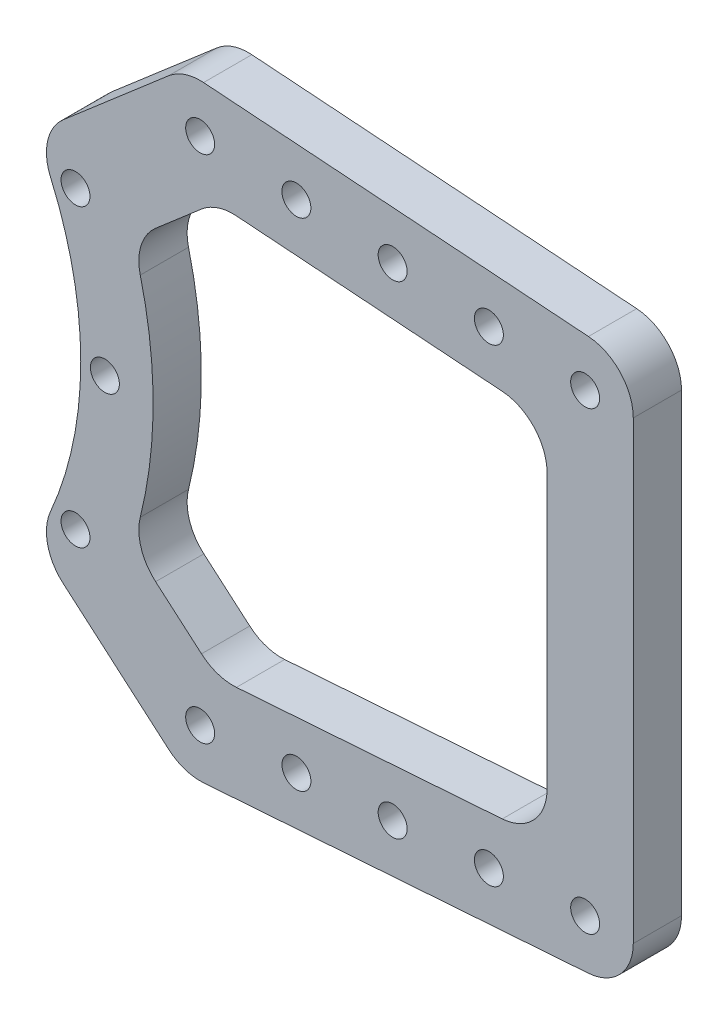
SolidWorks part; units mm, degrees
ref_plane "前视基准面" through (0, 0, 0) normal (0, 0, 1) x (1, 0, 0)
ref_plane "上视基准面" through (0, 0, 0) normal (0, 1, 0) x (1, 0, 0)
ref_plane "右视基准面" through (0, 0, 0) normal (1, 0, 0) x (0, 0, -1)
other "Configuration Table"
sketch "草图3" plane through (0, 0, 0) normal (0, 0, 1) x (1, 0, 0)
  line L0 (36.9552, -15.3073) -> (49.8729, -26.4376)
  line L1 (49.8729, -26.4376) -> (99.7459, -22.8753)
  line L2 (99.7459, -22.8753) -> (109.9739, -12.4372)
  line L3 (36.9552, 15.3073) -> (49.8729, 26.4376)
  line L4 (49.8729, 26.4376) -> (99.7459, 22.8753)
  line L5 (99.7459, 22.8753) -> (109.9739, 12.4372)
  line L6 (32.4388, -18.0159) -> (48.1718, -31.5719)
  line L7 (48.1718, -31.5719) -> (101.9915, -27.7276)
  line L8 (101.9915, -27.7276) -> (114.1851, -15.2836)
  line L9 (40.2189, -11.5195) -> (51.5741, -21.3034)
  line L10 (51.5741, -21.3034) -> (97.5003, -18.023)
  line L11 (97.5003, -18.023) -> (106.4026, -8.9378)
  line L12 (40.2189, 11.5195) -> (51.5741, 21.3034)
  line L13 (51.5741, 21.3034) -> (97.5003, 18.023)
  line L14 (97.5003, 18.023) -> (106.4026, 8.9378)
  line L15 (32.0167, 17.6522) -> (48.1718, 31.5719)
  line L16 (48.1718, 31.5719) -> (101.9915, 27.7276)
  line L17 (101.9915, 27.7276) -> (114.1732, 15.2957)
  line L18 (33.6914, -19.0952) -> (48.1718, -31.5719) construction
  line L19 (33.6914, 19.0952) -> (48.1718, 31.5719) construction
  line L20 (101.9915, -27.7276) -> (113.5452, -15.9366) construction
  line L21 (101.9915, 27.7276) -> (113.5452, 15.9366) construction
  line L22 (112.379, 17.1268) -> (115.1724, 14.276)
  circle A0 centre (140, 0) radius 32.5
  circle A1 centre (0, 0) radius 40
  circle A2 centre (140, 0) radius 35
  circle A4 centre (0, 0) radius 45
  circle A5 centre (0, 0) radius 37.5
  circle A6 centre (140, 0) radius 30
  dimension "D5" = 75
  dimension "D6" = 60
  dimension "D1" = 5
  dimension "D2" = 5
  dimension "D3" = 5
  dimension "D4" = 5
extrude "凸台-拉伸1" add sketch "草图3" along normal blind 15
fillet "圆角1" radius 5 1 edges at (101.9915, 27.7276, 7.5)
fillet "圆角2" radius 5 1 edges at (114.1851, 15.2836, 7.5)
fillet "圆角3" radius 5 1 edges at (114.1851, -15.2836, 7.5)
fillet "圆角4" radius 5 1 edges at (101.9915, -27.7276, 7.5)
fillet "圆角5" radius 5 1 edges at (48.1718, -31.5719, 7.5)
fillet "圆角6" radius 5 1 edges at (48.1718, 31.5719, 7.5)
fillet "圆角7" radius 5 1 edges at (32.7436, -18.2785, 7.5)
fillet "圆角8" radius 5 1 edges at (32.7436, 18.2785, 7.5)
fillet "圆角9" radius 5 1 edges at (97.5003, -18.023, 7.5)
fillet "圆角10" radius 5 1 edges at (106.2123, -9.132, 7.5)
fillet "圆角11" radius 5 1 edges at (106.2123, 9.132, 7.5)
fillet "圆角12" radius 5 1 edges at (97.5003, 18.023, 7.5)
fillet "圆角13" radius 5 1 edges at (51.5741, -21.3034, 7.5)
fillet "圆角14" radius 5 1 edges at (42.8391, -13.7771, 7.5)
fillet "圆角15" radius 5 1 edges at (42.8391, 13.7771, 7.5)
fillet "圆角16" radius 5 1 edges at (51.5741, 21.3034, 7.5)
sketch "草图5" plane through (0, 0, 0) normal (0, 0, -1) x (-1, 0, 0)
  circle A0 centre (-36.9552, 15.3073) radius 1.5
  circle A1 centre (-40, 0) radius 1.5
  circle A2 centre (-36.9552, -15.3073) radius 1.5
  circle A3 centre (-49.8729, -26.4376) radius 1.5
  circle A4 centre (-49.8729, 26.4376) radius 1.5
  circle A5 centre (-99.7459, 22.8753) radius 1.5
  circle A6 centre (-99.7459, -22.8753) radius 1.5
  circle A7 centre (-109.9739, 12.4372) radius 1.5
  circle A8 centre (-107.5, 0) radius 1.5
  circle A9 centre (-109.9739, -12.4372) radius 1.5
  circle A10 centre (-59.8475, 25.7252) radius 1.5
  circle A11 centre (-69.8221, 25.0127) radius 1.5
  circle A12 centre (-79.7967, 24.3002) radius 1.5
  circle A13 centre (-89.7713, 23.5878) radius 1.5
  circle A14 centre (-89.7713, -23.5878) radius 1.5
  circle A15 centre (-79.7967, -24.3002) radius 1.5
  circle A16 centre (-69.8221, -25.0127) radius 1.5
  circle A17 centre (-59.8475, -25.7252) radius 1.5
extrude "切除-拉伸1" cut sketch "草图5" against normal blind 15
sketch "草图6" plane through (0, 0, 15) normal (0, 0, 1) x (1, 0, 0)
  line L0 (100.1021, 27.8626) -> (100.1021, -27.8626)
  line L1 (100.1021, 27.8626) -> (115.1226, 26.777)
  line L2 (4.9746, 34.6447) -> (140, 25) construction
  line L3 (115.1226, 26.777) -> (132.6157, -67.8734)
  line L4 (132.6157, -67.8734) -> (100.1021, -27.8626)
  line L5 (99.7459, 22.8753) -> (89.7713, 23.5878)
  line L6 (99.7459, -22.8753) -> (89.7713, -23.5878)
  line L7 (94.7586, 23.2315) -> (94.7586, -23.2315)
  line L8 (94.7586, 23.2315) -> (94.7586, 28.2443)
  line L9 (50.2292, 31.4249) -> (100.1021, 27.8626) construction
  line L10 (94.7586, 28.2443) -> (100.1021, 27.8626)
  line L11 (94.7586, -23.2315) -> (94.7586, -28.2443)
  line L12 (50.2292, -31.4249) -> (100.1021, -27.8626) construction
  line L13 (94.7586, -28.2443) -> (100.1021, -27.8626)
  circle M8 centre (109.9739, -12.4372) radius 1.5
  circle M13 centre (107.5, 0) radius 1.5
  circle M14 centre (109.9739, 12.4372) radius 1.5
  circle M15 centre (99.7459, -22.8753) radius 1.5
  circle M16 centre (99.7459, 22.8753) radius 1.5
  line M24 (53.6315, 21.1564) -> (95.6109, 18.1579)
  arc M25 (95.6109, 18.1579) -> (98.826, 16.67) centre (95.2547, 13.1706) cw
  line M26 (98.826, 16.67) -> (104.2974, 11.0863)
  arc M27 (104.2974, 11.0863) -> (105.6353, 6.6385) centre (100.7261, 7.5869) cw
  arc M28 (105.6353, 6.6385) -> (105.6353, -6.6385) centre (140, 0) ccw
  arc M29 (105.6353, -6.6385) -> (104.2974, -11.0863) centre (100.7261, -7.5869) cw
  line M30 (104.2974, -11.0863) -> (98.826, -16.67)
  arc M31 (98.826, -16.67) -> (95.6109, -18.1579) centre (95.2547, -13.1706) cw
  line M32 (95.6109, -18.1579) -> (53.6315, -21.1564)
  line M45 (50.2292, -31.4249) -> (100.1021, -27.8626)
  arc M46 (100.1021, -27.8626) -> (103.3172, -26.3747) centre (99.7459, -22.8753) ccw
  line M47 (103.3172, -26.3747) -> (111.6554, -17.8652)
  arc M48 (111.6554, -17.8652) -> (112.6435, -12.3136) centre (108.0841, -14.3658) ccw
  arc M49 (112.6435, -12.3136) -> (112.6435, 12.3136) centre (140, 0) cw
  arc M50 (112.6435, 12.3136) -> (111.6554, 17.8652) centre (108.0841, 14.3658) ccw
  line M51 (111.6554, 17.8652) -> (103.3172, 26.3747)
  arc M52 (103.3172, 26.3747) -> (100.1021, 27.8626) centre (99.7459, 22.8753) ccw
  line M53 (100.1021, 27.8626) -> (50.2292, 31.4249)
extrude "切除-拉伸5" cut sketch "草图6" against normal blind 15 contours L0 M52 M16 M26 M27 M28 M29 M30 M15 M46 M47 M48 M49 M50 M51 M13 M14 M8 | L7 L6 L0 M32 M15 M30 M31 | L6 L11 L0 M45 M15 | L5 L7 L0 M24 M25 M26 M16 | L8 L5 L0 M16 M53
sketch "草图7" plane through (0, 0, 15) normal (0, 0, 1) x (1, 0, 0)
  line L0 (94.7586, 18.2188) -> (85.8268, 18.8568)
  line L1 (94.7586, 28.2443) -> (85.8268, 28.2443)
  line L2 (94.7586, 28.2443) -> (94.7586, -28.2443)
  line L3 (94.7586, -28.2443) -> (85.8268, -28.2443)
  line L4 (85.8268, 28.2443) -> (85.8268, -28.2443)
  line L5 (53.6315, 21.1564) -> (94.7586, 18.2188) construction
  line L6 (94.7586, -18.2188) -> (85.8268, -18.8568)
  line L7 (53.6315, -21.1564) -> (94.7586, -18.2188) construction
  line M3 (94.7586, -18.2188) -> (53.6315, -21.1564)
  line M11 (53.6315, 21.1564) -> (94.7586, 18.2188)
extrude "凸台-拉伸2" add sketch "草图7" against normal blind 15 contours L4 L2 M11 M3
fillet "圆角17" radius 5 1 edges at (94.7586, 28.2443, 7.5)
fillet "圆角18" radius 5 1 edges at (94.7586, -28.2443, 7.5)
fillet "圆角19" radius 5 1 edges at (85.8268, 18.8568, 7.5)
fillet "圆角20" radius 5 1 edges at (85.8268, -18.8568, 7.5)
sketch "草图8" plane through (0, 0, 0) normal (0, 0, -1) x (-1, 0, 0)
  line L1 (-115.5106, 32.3706) -> (-18.9905, 32.3706)
  line L2 (-115.5106, 32.3706) -> (-115.5106, -39.9455)
  line L3 (-115.5106, -39.9455) -> (-18.9905, -39.9455)
  line L4 (-18.9905, 32.3706) -> (-18.9905, -39.9455)
  line L5 (-115.5106, 32.3706) -> (-18.9905, -39.9455) construction
  line L6 (-115.5106, -39.9455) -> (-18.9905, 32.3706) construction
  point P0 (-67.2506, -3.7874)
extrude "切除-拉伸6" cut sketch "草图8" against normal blind 5
sketch "草图9" plane through (0, 0, 15) normal (0, 0, 1) x (1, 0, 0)
  line L1 (18.8961, 40.6997) -> (110.1124, 40.6997)
  line L2 (18.8961, 40.6997) -> (18.8961, -39.268)
  line L3 (18.8961, -39.268) -> (110.1124, -39.268)
  line L4 (110.1124, 40.6997) -> (110.1124, -39.268)
  line L5 (18.8961, 40.6997) -> (110.1124, -39.268) construction
  line L6 (18.8961, -39.268) -> (110.1124, 40.6997) construction
  point P0 (64.5042, 0.7158)
extrude "切除-拉伸7" cut sketch "草图9" against normal blind 5
